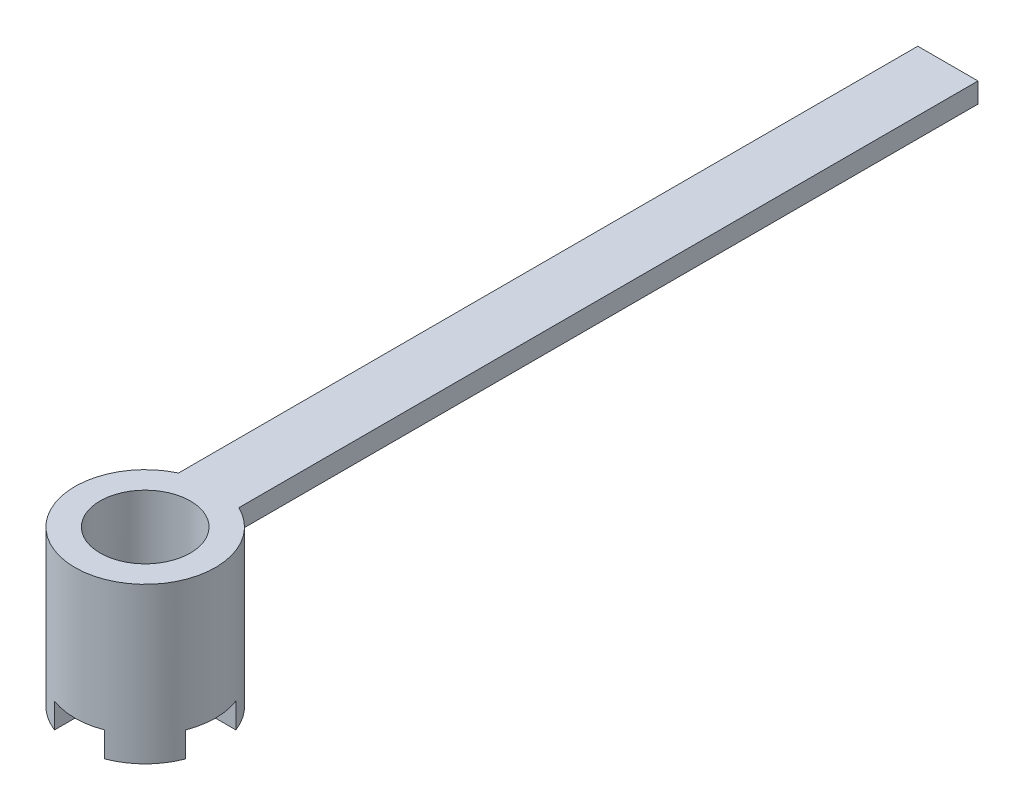
SolidWorks part; units mm, degrees
ref_plane "Front Plane" through (0, 0, 0) normal (0, 0, 1) x (1, 0, 0)
ref_plane "Top Plane" through (0, 0, 0) normal (0, 1, 0) x (1, 0, 0)
ref_plane "Right Plane" through (0, 0, 0) normal (1, 0, 0) x (0, 0, -1)
sketch "Sketch2" plane through (0, 0, 0) normal (0, 1, 0) x (1, 0, 0)
  line L1 (3.81, 101.6) -> (-3.81, 101.6)
  line L2 (3.81, 101.6) -> (3.81, 0)
  line L3 (3.81, 0) -> (-3.81, 0)
  line L4 (-3.81, 101.6) -> (-3.81, 0)
  circle A0 centre (0, 0) radius 8.89
  circle A1 centre (0, 0) radius 5.715
  point P8 (0, 0)
  dimension "D1" = 17.78
  dimension "D2" = 11.43
  dimension "D3" = 7.62
  dimension "D4" = 101.6
extrude "Boss-Extrude1" add sketch "Sketch2" along normal blind 2.54 contours A0 L2 L1 L4 | A1 L2 A0 L4 | A1 L4 A0 L2
sketch "Sketch3" plane through (0, 0, 0) normal (0, -1, 0) x (1, 0, 0)
  circle A0 centre (0, 0) radius 8.89
  circle A1 centre (0, 0) radius 5.715
extrude "Boss-Extrude2" add sketch "Sketch3" along normal blind 17.145
sketch "Sketch4" plane through (0, -17.145, 0) normal (0, -1, 0) x (1, 0, 0)
  line L1 (-3.175, 12.7) -> (3.175, 12.7)
  line L2 (-3.175, 12.7) -> (-3.175, -12.7)
  line L3 (-3.175, -12.7) -> (3.175, -12.7)
  line L4 (3.175, 12.7) -> (3.175, -12.7)
  line L5 (-12.7, 3.175) -> (12.7, 3.175)
  line L6 (-12.7, 3.175) -> (-12.7, -3.175)
  line L7 (-12.7, -3.175) -> (12.7, -3.175)
  line L8 (12.7, 3.175) -> (12.7, -3.175)
  circle A0 centre (0, 0) radius 5.715 construction
  circle A1 centre (0, 0) radius 5.715
  point P4 (0, 12.7)
  point P6 (3.175, 0)
  point P11 (0, 3.175)
  point P12 (12.7, 0)
  circle M1 centre (0, 0) radius 8.89
  circle M2 centre (0, 0) radius 5.715
  dimension "D1" = 25.4
  dimension "D2" = 6.35
  dimension "D3" = 6.35
  dimension "D4" = 25.4
extrude "Cut-Extrude1" cut sketch "Sketch4" against normal blind 3.175 contours L7 L5 M1 M2 | L4 L2 M1 M2 | L7 L5 M2 M1 | L4 L2 M2 M1
equation "\"D3@Sketch4\"=\"D2@Sketch4\""
equation "\"D4@Sketch4\"=\"D1@Sketch4\""
